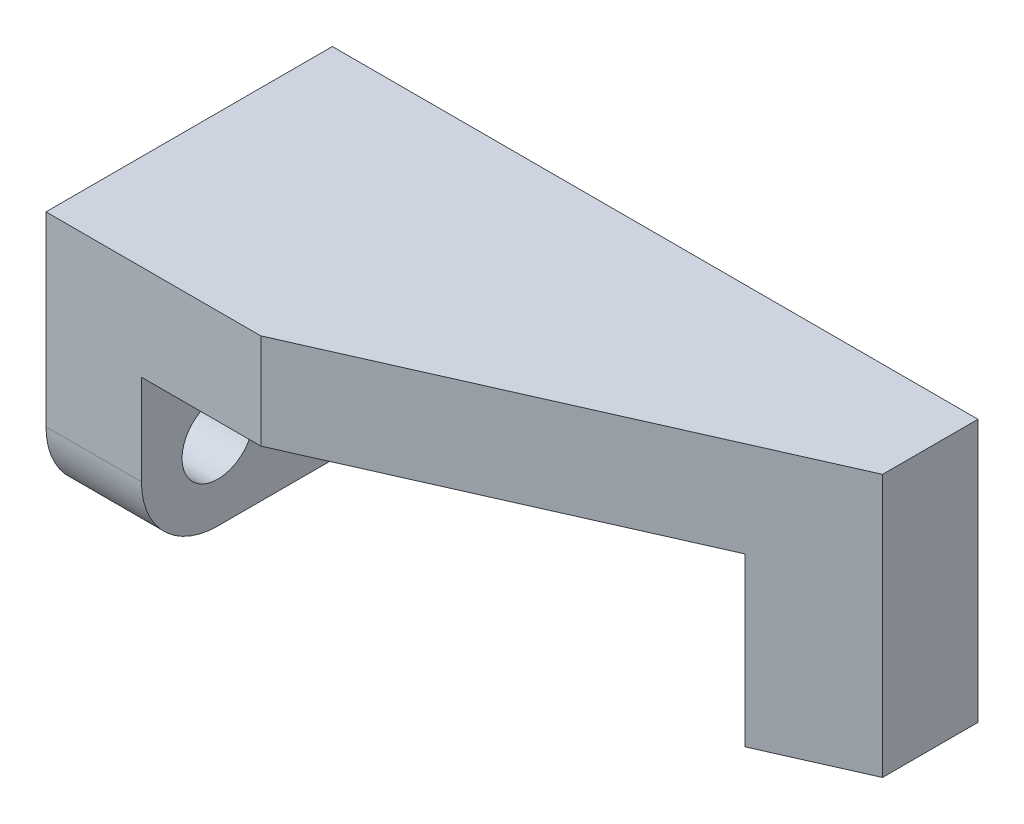
SolidWorks part; units mm, degrees
ref_plane "정면" through (0, 0, 0) normal (0, 0, 1) x (1, 0, 0)
ref_plane "윗면" through (0, 0, 0) normal (0, 1, 0) x (1, 0, 0)
ref_plane "우측면" through (0, 0, 0) normal (1, 0, 0) x (0, 0, -1)
sketch "Sketch3" plane through (0, 0, 0) normal (0, 0, 1) x (1, 0, 0)
  line L3 (-47.6344, -55) -> (-47.6344, -20)
  line L4 (-47.6344, -20) -> (47.6344, -20)
  line L5 (47.6344, -20) -> (47.6344, -55)
  line L6 (-67.6344, -55) -> (-67.6344, 0)
  line L7 (-67.6344, 0) -> (67.6344, 0)
  line L8 (67.6344, 0) -> (67.6344, -55)
  line L9 (-47.6344, -55) -> (-67.6344, -55)
  line L10 (47.6344, -55) -> (67.6344, -55)
  point P0 (0, 0)
  dimension "D1" = 20
  dimension "D2" = 20
  dimension "D3" = 55
  dimension "D4" = 20
  dimension "D5" = 55
extrude "Boss-Extrude3" add sketch "Sketch3" along normal blind 60 contours L8 L10 L5 L4 L3 L9 L6 L7
sketch "Sketch4" plane through (0, -20, 0) normal (0, -1, 0) x (1, 0, 0)
  line L0 (-22.6344, 60) -> (67.6344, 60)
  line L1 (-47.6344, 60) -> (47.6344, 60) construction
  line L2 (67.6344, 60) -> (67.6344, 0) construction
  line L3 (67.6344, 60) -> (67.6344, 20)
  line L4 (67.6344, 20) -> (-22.6344, 60)
  line L5 (-67.6344, 60) -> (-67.6344, 0) construction
  line L6 (47.6344, 0) -> (67.6344, 0) construction
  dimension "D1" = 45
  dimension "D2" = 20
extrude "Cut-Extrude1" cut sketch "Sketch4" against normal through all both and the other way through all contours L4 L0 L3
fillet "Fillet3" radius 16 1 edges at (-57.6344, -55, 60)
sketch "Sketch7" plane through (-47.6344, 0, 0) normal (1, 0, 0) x (0, 0, -1)
  circle A0 centre (-44, -39) radius 7.5
extrude "Cut-Extrude2" cut sketch "Sketch7" against normal blind 100 contours A0
